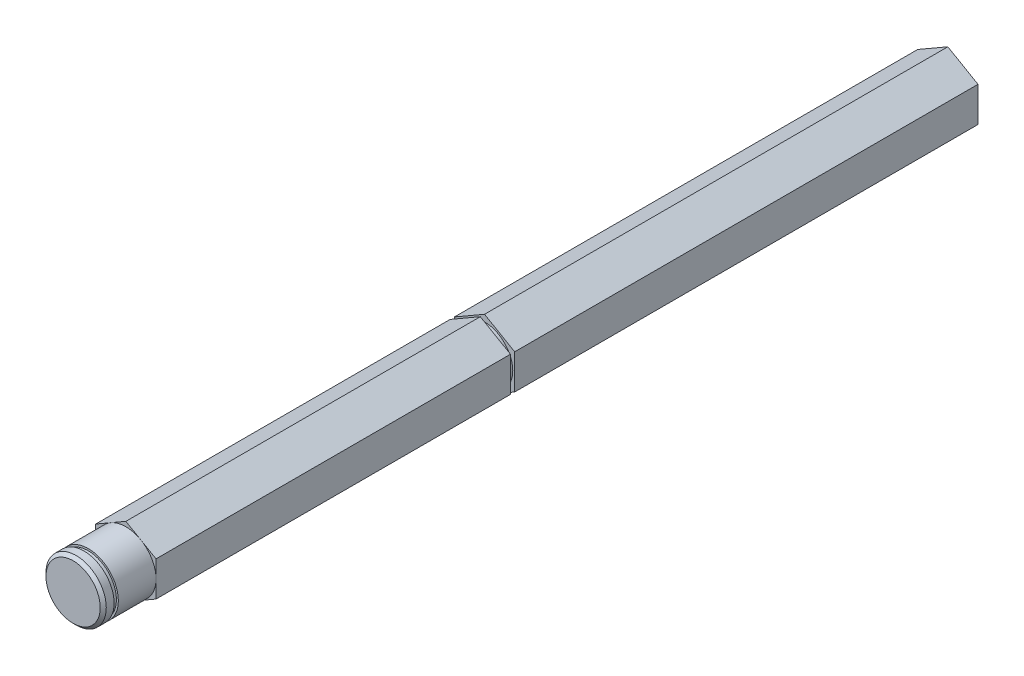
SolidWorks part; units mm, degrees
ref_plane "Front Plane" through (0, 0, 0) normal (0, 0, 1) x (1, 0, 0)
ref_plane "Top Plane" through (0, 0, 0) normal (0, 1, 0) x (1, 0, 0)
ref_plane "Right Plane" through (0, 0, 0) normal (1, 0, 0) x (0, 0, -1)
sketch "Sketch1" plane through (0, 0, 0) normal (0, 0, 1) x (1, 0, 0)
  line L1 (0, 7.3323) -> (-6.35, 3.6662)
  line L2 (-6.35, 3.6662) -> (-6.35, -3.6662)
  line L3 (-6.35, -3.6662) -> (0, -7.3323)
  line L4 (0, -7.3323) -> (6.35, -3.6662)
  line L5 (6.35, -3.6662) -> (6.35, 3.6662)
  line L6 (6.35, 3.6662) -> (0, 7.3323)
  circle A0 centre (0, 0) radius 6.35 construction
  dimension "D1" = 12.7
extrude "Boss-Extrude1" add sketch "Sketch1" along normal blind 184.15
sketch "Sketch2" plane through (0, 0, 184.15) normal (0, 0, 1) x (1, 0, 0)
  circle A0 centre (0, 0) radius 6.35
  circle A1 centre (0, 0) radius 7.3323
extrude "Cut-Extrude1" cut sketch "Sketch2" against normal blind 11.1125
sketch "Sketch3" plane through (0, 0, 0) normal (1, 0, 0) x (0, 0, -1)
  line L0 (-184.15, 0) -> (0, 0) construction
  line L1 (-184.15, 6.35) -> (-184.15, -6.35) construction
  line L2 (-173.0375, 6.35) -> (-184.15, 6.35) construction
  line L3 (-181.864, 6.35) -> (-180.975, 6.35)
  line L4 (-181.864, 6.35) -> (-181.864, 5.9436)
  line L5 (-181.864, 5.9436) -> (-180.975, 5.9436)
  line L6 (-180.975, 6.35) -> (-180.975, 5.9436)
  line L7 (-184.15, 6.35) -> (0, 6.35) construction
  line L8 (0, 3.6662) -> (0, 7.3323) construction
  line L10 (-98.425, 8.9817) -> (-97.536, 8.9817)
  line L11 (-98.425, 8.9817) -> (-98.425, 5.9436)
  line L12 (-98.425, 5.9436) -> (-97.536, 5.9436)
  line L13 (-97.536, 8.9817) -> (-97.536, 5.9436)
  dimension "D1" = 0.889
  dimension "D2" = 3.175
  dimension "D3" = 5.9436
  dimension "D4" = 0.889
  dimension "D5" = 82.55
revolve "Cut-Revolve1" cut sketch "Sketch3" angle 360 about L0
chamfer "Chamfer1" distance 0.635 angle 45 1 edges at (6.35, 0, 184.15)
equation "\"D3@Sketch3\"=0.468/2"
